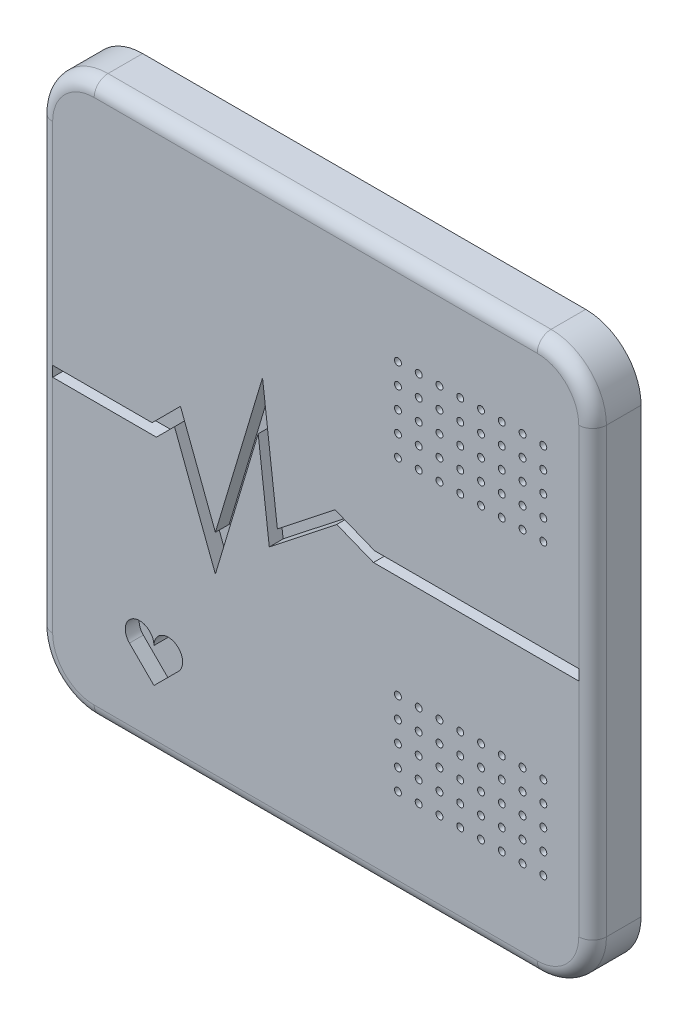
SolidWorks part; units mm, degrees
material "ABS"
ref_plane "Plan de face" through (0, 0, 0) normal (0, 0, 1) x (1, 0, 0)
ref_plane "Plan de dessus" through (0, 0, 0) normal (0, 1, 0) x (1, 0, 0)
ref_plane "Plan de droite" through (0, 0, 0) normal (1, 0, 0) x (0, 0, -1)
sketch "Esquisse1" plane through (0, 0, 0) normal (0, 0, 1) x (1, 0, 0)
  line L1 (-40, 40) -> (40, 40)
  line L2 (-40, 40) -> (-40, -40)
  line L3 (-40, -40) -> (40, -40)
  line L4 (40, 40) -> (40, -40)
  line L5 (-40, 40) -> (40, -40) construction
  line L6 (-40, -40) -> (40, 40) construction
  point P0 (0, 0)
  dimension "D1" = 80
  dimension "D2" = 80
extrude "Boss.-Extru.1" add sketch "Esquisse1" along normal blind 7
fillet "Congé1" radius 8 4 edges at (-40, -40, 3.5) (-40, 40, 3.5) (40, -40, 3.5) (40, 40, 3.5)
fillet "Congé2" radius 2 8 edges at (37.6569, -37.6569, 7) (0, -40, 7) (-37.6569, -37.6569, 7) (-40, 0, 7) (-37.6569, 37.6569, 7) (0, 40, 7) (37.6569, 37.6569, 7) (40, 0, 7)
sketch "Esquisse2" plane through (0, 0, 0) normal (0, 0, -1) x (-1, 0, 0)
  line L1 (-37.5, 37.5) -> (37.5, 37.5)
  line L2 (-37.5, 37.5) -> (-37.5, -37.5)
  line L3 (-37.5, -37.5) -> (37.5, -37.5)
  line L4 (37.5, 37.5) -> (37.5, -37.5)
  line L5 (-37.5, 37.5) -> (37.5, -37.5) construction
  line L6 (-37.5, -37.5) -> (37.5, 37.5) construction
  point P0 (0, 0)
  dimension "D1" = 75
  dimension "D2" = 75
extrude "Enlèv. mat.-Extru.1" cut sketch "Esquisse2" against normal blind 4
sketch "Esquisse3" plane through (0, 0, 7) normal (0, 0, 1) x (1, 0, 0)
  line L0 (-38, 0) -> (-23.0131, 0)
  line L1 (-23.0131, 0) -> (-20.391, 2.6221)
  line L6 (-38, 1.5) -> (-23.6344, 1.5)
  line L7 (-38, 32) -> (-38, -32) construction
  line L8 (-23.6344, 1.5) -> (-19.5339, 5.6004)
  line L9 (-20.391, 2.6221) -> (-16.096, -8.6578)
  line L10 (-19.5339, 5.6004) -> (-14.4912, -7.6432)
  line L11 (-14.4912, -7.6432) -> (-7.6781, 15.1098)
  line L12 (-7.6781, 15.1098) -> (-5.5357, -2.7465)
  line L13 (-5.5357, -2.7465) -> (2.7978, 3.8245)
  line L14 (2.7978, 3.8245) -> (8.4988, 1.5522)
  line L15 (8.4988, 1.5522) -> (38, 1.5522)
  line L16 (38, -32) -> (38, 32) construction
  line L17 (-16.096, -8.6578) -> (-14.4912, -12.8724)
  line L18 (-14.4912, -12.8724) -> (-8.3088, 7.7745)
  line L19 (-8.3088, 7.7745) -> (-6.7065, -5.5799)
  line L20 (-6.7065, -5.5799) -> (3.0467, 2.1105)
  line L21 (3.0467, 2.1105) -> (8.3417, 0)
  line L22 (8.3417, 0) -> (38, 0)
  line L23 (38, 1.5522) -> (38, 0)
  line L24 (-38, 1.5) -> (-38, 0)
  dimension "D1" = 1.5
  dimension "D2" = 1.5
  dimension "D3" = 1.5
  dimension "D4" = 1.5
  dimension "D5" = 1.5
  dimension "D6" = 1.5
extrude "Enlèv. mat.-Extru.2" cut sketch "Esquisse3" against normal blind 2
sketch "Esquisse4" plane through (0, 0, 7) normal (0, 0, 1) x (1, 0, 0)
  line L2 (-26.9035, -27.705) -> (-23.365, -31.2435)
  line L3 (-23.365, -31.2435) -> (-19.8264, -27.705)
  arc A2 (-19.8264, -27.705) -> (-23.365, -26.2392) centre (-21.2921, -26.2392) ccw
  arc A3 (-23.365, -26.2392) -> (-26.9035, -27.705) centre (-25.4378, -26.2392) ccw
extrude "Enlèv. mat.-Extru.3" cut sketch "Esquisse4" against normal blind 2
sketch "Esquisse6" plane through (0, 0, 7) normal (0, 0, 1) x (1, 0, 0)
  circle A0 centre (11.8792, 26.8782) radius 0.5
  circle A1 centre (14.8792, 26.8782) radius 0.5
  circle A2 centre (17.8792, 26.8782) radius 0.5
  circle A3 centre (20.8792, 26.8782) radius 0.5
  circle A4 centre (23.8792, 26.8782) radius 0.5
  circle A5 centre (26.8792, 26.8782) radius 0.5
  circle A6 centre (29.8792, 26.8782) radius 0.5
  circle A7 centre (32.8792, 26.8782) radius 0.5
  circle A8 centre (14.8792, 23.8782) radius 0.5
  circle A9 centre (17.8792, 23.8782) radius 0.5
  circle A10 centre (20.8792, 23.8782) radius 0.5
  circle A11 centre (23.8792, 23.8782) radius 0.5
  circle A12 centre (26.8792, 23.8782) radius 0.5
  circle A13 centre (29.8792, 23.8782) radius 0.5
  circle A14 centre (32.8792, 23.8782) radius 0.5
  circle A15 centre (14.8792, 20.8782) radius 0.5
  circle A16 centre (17.8792, 20.8782) radius 0.5
  circle A17 centre (20.8792, 20.8782) radius 0.5
  circle A18 centre (23.8792, 20.8782) radius 0.5
  circle A19 centre (26.8792, 20.8782) radius 0.5
  circle A20 centre (29.8792, 20.8782) radius 0.5
  circle A21 centre (32.8792, 20.8782) radius 0.5
  circle A22 centre (14.8792, 17.8782) radius 0.5
  circle A23 centre (17.8792, 17.8782) radius 0.5
  circle A24 centre (20.8792, 17.8782) radius 0.5
  circle A25 centre (23.8792, 17.8782) radius 0.5
  circle A26 centre (26.8792, 17.8782) radius 0.5
  circle A27 centre (29.8792, 17.8782) radius 0.5
  circle A28 centre (32.8792, 17.8782) radius 0.5
  circle A29 centre (14.8792, 14.8782) radius 0.5
  circle A30 centre (17.8792, 14.8782) radius 0.5
  circle A31 centre (20.8792, 14.8782) radius 0.5
  circle A32 centre (23.8792, 14.8782) radius 0.5
  circle A33 centre (26.8792, 14.8782) radius 0.5
  circle A34 centre (29.8792, 14.8782) radius 0.5
  circle A35 centre (32.8792, 14.8782) radius 0.5
  circle A36 centre (11.8792, 23.8782) radius 0.5
  circle A37 centre (11.8792, 20.8782) radius 0.5
  circle A38 centre (11.8792, 17.8782) radius 0.5
  circle A39 centre (11.8792, 14.8782) radius 0.5
  dimension "D1" = 1
  dimension "D2" = 8
  dimension "D3" = 5
extrude "Enlèv. mat.-Extru.4" cut sketch "Esquisse6" against normal through all
mirror "Symétrie2" about plane through (0, 0, 0) normal (0, 1, 0) of "Enlèv. mat.-Extru.4"
fillet "Congé3" radius 3 4 edges at (-37.5, -37.5, 2) (-37.5, 37.5, 2) (37.5, 37.5, 2) (37.5, -37.5, 2)
